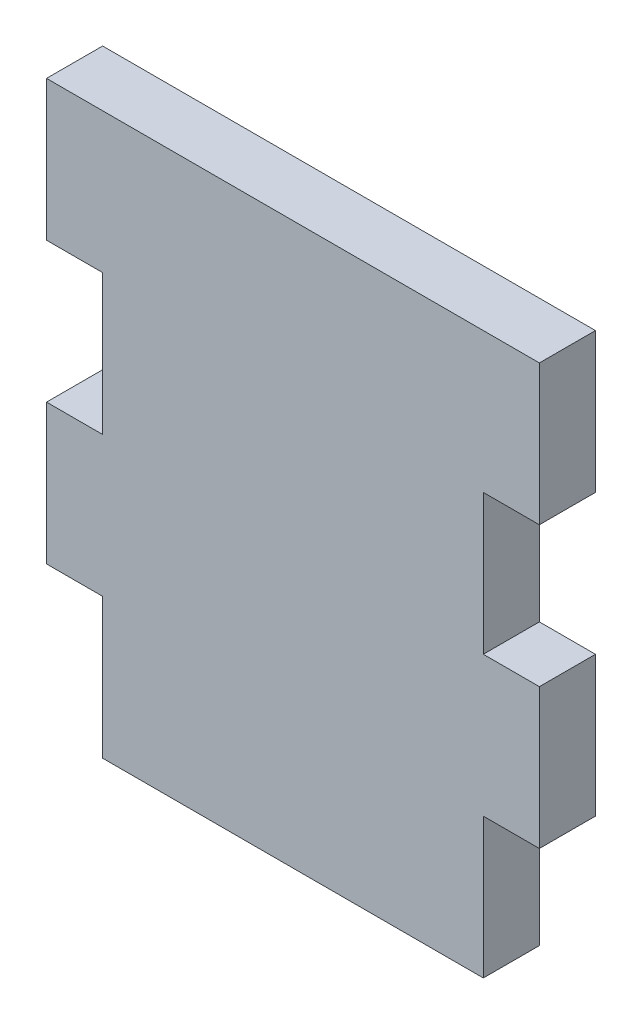
SolidWorks part; units mm, degrees
ref_plane "Front Plane" through (0, 0, 0) normal (0, 0, 1) x (1, 0, 0)
ref_plane "Top Plane" through (0, 0, 0) normal (0, 1, 0) x (1, 0, 0)
ref_plane "Right Plane" through (0, 0, 0) normal (1, 0, 0) x (0, 0, -1)
sketch "Sketch1" plane through (0, 0, 0) normal (0, 0, 1) x (1, 0, 0)
  line L1 (-88.0852, 14.1109) -> (-45.6672, 14.1109)
  line L2 (-88.0852, 14.1109) -> (-88.0852, -34.1491)
  line L3 (-88.0852, -34.1491) -> (-45.6672, -34.1491)
  line L4 (-45.6672, 14.1109) -> (-45.6672, -34.1491)
  dimension "D1" = 48.26
  dimension "D2" = 42.418
extrude "Boss-Extrude1" add sketch "Sketch1" along normal blind 4.826
sketch "Sketch2" plane through (0, 0, 4.826) normal (0, 0, 1) x (1, 0, 0)
  line L0 (-88.0852, 14.1109) -> (-88.0852, -34.1491) construction
  line L1 (-88.0852, -34.1491) -> (-83.2592, -34.1491)
  line L2 (-88.0852, -34.1491) -> (-88.0852, -22.0841)
  line L3 (-88.0852, -22.0841) -> (-83.2592, -22.0841)
  line L4 (-83.2592, -34.1491) -> (-83.2592, -22.0841)
  line L5 (-88.0852, -10.0191) -> (-83.2592, -10.0191)
  line L6 (-88.0852, -10.0191) -> (-88.0852, 2.0459)
  line L7 (-88.0852, 2.0459) -> (-83.2592, 2.0459)
  line L8 (-83.2592, -10.0191) -> (-83.2592, 2.0459)
  line L9 (-83.2592, 2.0459) -> (-83.2592, 14.1109) construction
  line L10 (-45.6672, 14.1109) -> (-88.0852, 14.1109) construction
  line L11 (-83.2592, -10.0191) -> (-83.2592, -22.0841) construction
  line L12 (-66.8762, 14.1109) -> (-66.8762, -34.1491) construction
  line L13 (-88.0852, -34.1491) -> (-45.6672, -34.1491) construction
  line L14 (-50.4932, -10.0191) -> (-50.4932, -22.0841) construction
  line L15 (-50.4932, 2.0459) -> (-50.4932, 14.1109) construction
  line L16 (-50.4932, -10.0191) -> (-50.4932, 2.0459)
  line L17 (-45.6672, 2.0459) -> (-50.4932, 2.0459)
  line L18 (-45.6672, -10.0191) -> (-45.6672, 2.0459)
  line L19 (-45.6672, -10.0191) -> (-50.4932, -10.0191)
  line L20 (-50.4932, -34.1491) -> (-50.4932, -22.0841)
  line L21 (-45.6672, -22.0841) -> (-50.4932, -22.0841)
  line L22 (-45.6672, -34.1491) -> (-45.6672, -22.0841)
  line L23 (-45.6672, -34.1491) -> (-50.4932, -34.1491)
  dimension "D1" = 4.826
extrude "Cut-Extrude1" cut sketch "Sketch2" against normal through all
equation "\"MDF\"= 0.19in"
equation "\"Foamcore\"= .13in"
equation "\"Gmaterial\"= \"MDF\""
equation "\"D1@Boss-Extrude1\"=\"MDF\""
equation "\"D1@Sketch2\"=\"MDF\""
equation "\"D2@Sketch1\"=\"MDF\"+\"MDF\"+1.29"
equation "\"PVCID\" = 2.067in"
equation "\"PVCOD\" = 2.375in"
equation "\"GenDiameter\"= 60mm"
equation "\"GenCutDiameter\" = 1.8in"
equation "\"GenCutDistance\" = 1"
equation "\"TowerHeight\" = 6in"
equation "\"TowerFrontBase\" = 3in"
equation "\"FunnelHeight\" = 1in"
equation "\"FunnelAngle\" = 20"
equation "\"TowerSideBase\" = 3in"
equation "\"TowerPanelLength\" = 2in"
equation "\"TowerPanelLeeway\" = 0.5in"
equation "\"BaseLength\" = 10in"
equation "\"BaseWidth\" = 10.5in"
equation "\"WheelHoleLength\" = 3.25in"
equation "\"WheelHoleWidth\" = 26mm"
equation "\"WheelHoleFromBack\" = 1in"
equation "\"DropLength\" = 1in"
equation "\"DropWidth\" = 8.5in"
equation "\"BumperWidth\" = 1in"
equation "\"HoleDiameter\" = 0.25in"
equation "\"SmallHexDiameter\" = 0.185in"
equation "\"SmallHexHeight\" = 0.701in"
equation "\"ScrewSize\" = 0.106in"
equation "\"BigHexDiameter\" = 0.251in"
equation "\"BigHexHeight\" = 0.374in"
equation "\"PCBThickness\" = 0.066in"
equation "\"ConnectorHeight\" = 0.517in"
equation "\"BoardHeight\" = 0.583in"
equation "\"UnoStackHeight\" = 1.351in"
equation "\"UnoStackWidth\" = 3.053in"
equation "\"UnoStackLength\" = 3.152in"
equation "\"HBridgeWidth\" = 1.797in"
equation "\"HBridgeLength\" = 2.236in"
equation "\"DSWidth\" = 1.820in"
equation "\"DSLength\" = 1.833in"
equation "\"StepperWidth\" = 1.799in"
equation "\"StepperLength\" = 2.248in"
equation "\"ULNWidth\" = 1.304in"
equation "\"ULNLength\" = 1.545in"
equation "\"VSwitchHeight\" = 0.392in"
equation "\"VSwitchWidth\" = 0.637in"
equation "\"VSwitchLength\" = 1.097in"
equation "\"SkateWheelDiameter\" = 80mm"
equation "\"SkateWheelThickness\" = 24mm"
equation "\"BaseDistance\" = 3in"
